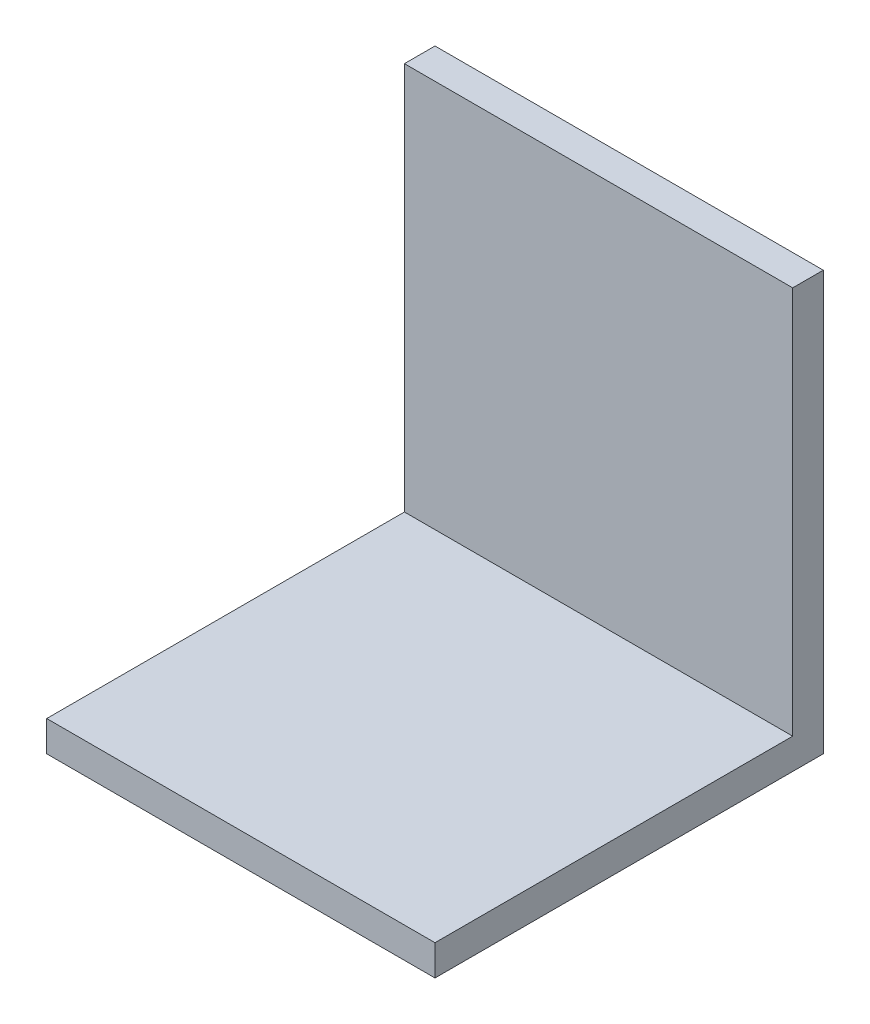
SolidWorks part; units mm, degrees
ref_plane "Front" through (0, 0, 0) normal (0, 0, 1) x (1, 0, 0)
ref_plane "Top" through (0, 0, 0) normal (0, 1, 0) x (1, 0, 0)
ref_plane "Right" through (0, 0, 0) normal (1, 0, 0) x (0, 0, -1)
sketch "草图4" plane through (0, 0, 0) normal (0, 1, 0) x (1, 0, 0)
  line L1 (-25.9474, 10.0148) -> (-0.5474, 10.0148)
  line L2 (-25.9474, 10.0148) -> (-25.9474, -15.3852)
  line L3 (-25.9474, -15.3852) -> (-0.5474, -15.3852)
  line L4 (-0.5474, 10.0148) -> (-0.5474, -15.3852)
extrude "凸台-拉伸2" add sketch "草图4" along normal blind 2 contours L3 L4 L1 L2
ref_plane "基准面1" through (-25.9474, 2, 15.3852) normal (1, 0, 0) x (0, 0, -1)
sketch "草图5" plane through (-25.9474, 2, 15.3852) normal (1, 0, 0) x (0, 0, -1)
  line L1 (25.4, 0) -> (0, 0)
  line L2 (25.4, 0) -> (25.4, -2)
  line L3 (25.4, -2) -> (0, -2)
  line L4 (0, 0) -> (0, -2)
extrude "凸台-拉伸3" add sketch "草图5" along normal blind 2
sketch "草图6" plane through (0, 2, 0) normal (0, 1, 0) x (1, 0, 0)
  line L0 (-0.5474, 10.0148) -> (-0.5474, -15.3852) construction
  line L1 (-25.9474, 10.0148) -> (-0.5474, 10.0148)
  line L2 (-25.9474, 10.0148) -> (-25.9474, 8.0148)
  line L3 (-25.9474, 8.0148) -> (-0.5474, 8.0148)
  line L4 (-0.5474, 10.0148) -> (-0.5474, 8.0148)
extrude "凸台-拉伸4" add sketch "草图6" along normal blind 25.4 contours L3 L4 L1 L2
